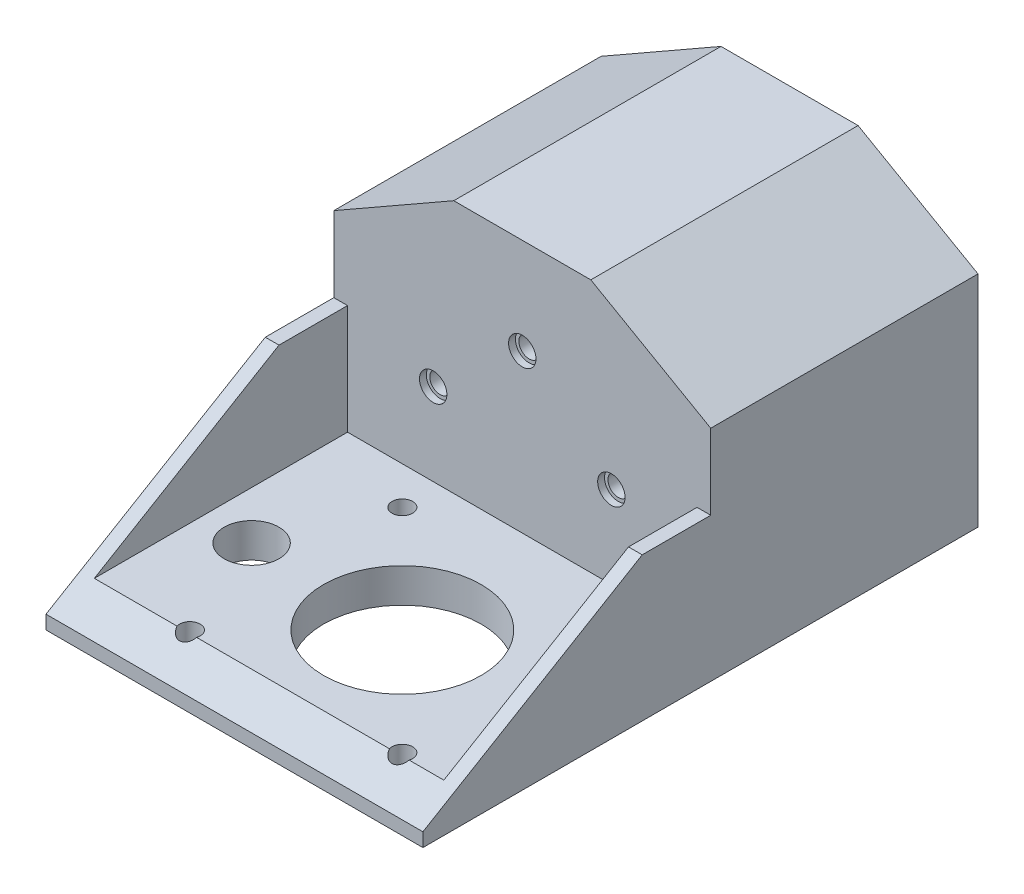
SolidWorks part; units mm, degrees
material "ABS"
ref_plane "Front Plane" through (0, 0, 0) normal (0, 0, 1) x (1, 0, 0)
ref_plane "Top Plane" through (0, 0, 0) normal (0, 1, 0) x (1, 0, 0)
ref_plane "Right Plane" through (0, 0, 0) normal (1, 0, 0) x (0, 0, -1)
sketch "Sketch1" plane through (0, 0, 0) normal (0, 0, 1) x (1, 0, 0)
  line L0 (0, 0) -> (55, 0)
  line L1 (55, 0) -> (55, 32)
  line L2 (55, 32) -> (37.5, 42)
  line L3 (37.5, 42) -> (17.5, 42)
  line L4 (17.5, 42) -> (0, 32)
  line L5 (0, 32) -> (0, 0)
  dimension "D1" = 55
  dimension "D2" = 42
  dimension "D3" = 32
  dimension "D4" = 20
extrude "Boss-Extrude1" add sketch "Sketch1" along normal blind 39
sketch "Sketch2" plane through (0, 0, 39) normal (0, 0, 1) x (1, 0, 0)
  line L0 (55, 0) -> (55, 32) construction
  line L1 (55, 5) -> (0, 5)
  line L2 (55, 5) -> (55, 0)
  line L3 (55, 0) -> (0, 0)
  line L4 (0, 5) -> (0, 0)
  dimension "D1" = 5
extrude "Boss-Extrude2" add sketch "Sketch2" along normal blind 42
sketch "Sketch3" plane through (0, 5, 0) normal (0, 1, 0) x (1, 0, 0)
  line L0 (55, -81) -> (55, -39) construction
  line L5 (31, -60) -> (31, -18) construction
  line L6 (31, -60) -> (63.5225, -60) construction
  line L8 (55, -39) -> (0, -39) construction
  circle A1 centre (15.5, -44.5) radius 1.5
  circle A2 centre (46.5, -44.5) radius 1.5
  circle A3 centre (46.5, -75.5) radius 1.5
  circle A4 centre (15.5, -75.5) radius 1.5
  circle A5 centre (9, -60) radius 4
  circle A6 centre (31, -60) radius 11.5
  dimension "D2" = 23
  dimension "D3" = 24
  dimension "D4" = 31
  dimension "D5" = 31
  dimension "D6" = 15.5
  dimension "D7" = 15.5
  dimension "D8" = 3
  dimension "D9" = 22
  dimension "D10" = 8
  dimension "D13" = 21
  dimension "D12" = 21
extrude "Cut-Extrude1" cut sketch "Sketch3" against normal through all
sketch "Sketch4" plane through (0, 0, 39) normal (0, 0, 1) x (1, 0, 0)
  line L0 (27.5, 43.7016) -> (27.5, -3.1108) construction
  line L1 (55, 5) -> (55, 32) construction
  line L2 (55, 5) -> (0, 5) construction
  line L3 (37.5, 42) -> (17.5, 42) construction
  line L4 (27.5, 47.161) -> (27.5, -7.3668) construction
  circle A0 centre (27.5, 28) radius 1.5
  circle A1 centre (40.5, 17) radius 1.5
  circle A3 centre (14.5, 17) radius 1.5
  dimension "D2" = 3
  dimension "D3" = 12
  dimension "D5" = 14
  dimension "D6" = 27.5
  dimension "D4" = 13
extrude "Cut-Extrude2" cut sketch "Sketch4" against normal through all
sketch "Sketch5" plane through (0, 0, 39) normal (0, 0, 1) x (1, 0, 0)
  circle A0 centre (27.5, 28) radius 2
  circle A1 centre (40.5, 17) radius 2
  circle A2 centre (14.5, 17) radius 2
  dimension "D1" = 4
extrude "Cut-Extrude3" cut sketch "Sketch5" against normal blind 1
sketch "Sketch6" plane through (0, 5, 0) normal (0, 1, 0) x (1, 0, 0)
  line L0 (55, -81) -> (0, -81) construction
  line L1 (0, -39) -> (2, -39)
  line L2 (0, -39) -> (0, -81)
  line L3 (0, -81) -> (2, -81)
  line L4 (2, -39) -> (2, -81)
  line L5 (55, -39) -> (0, -39) construction
  line L6 (55, -39) -> (53, -39)
  line L7 (55, -39) -> (55, -81)
  line L8 (55, -81) -> (53, -81)
  line L9 (53, -39) -> (53, -81)
  line L10 (55, -81) -> (55, -39) construction
  dimension "D1" = 2
  dimension "D2" = 2
extrude "Boss-Extrude3" add sketch "Sketch6" along normal blind 16
sketch "Sketch7" plane through (55, 0, 0) normal (1, 0, 0) x (0, 0, -1)
  line L0 (-49, 21) -> (-81, 21)
  line L1 (-81, 0) -> (-81, 21) construction
  line L2 (-81, 2) -> (-49, 21)
  line L3 (-81, 21) -> (-39, 21) construction
  line L4 (-81, 21) -> (-81, 2)
  line L5 (-81, 0) -> (0, 0) construction
  dimension "D1" = 2
  dimension "D2" = 32
extrude "Cut-Extrude4" cut sketch "Sketch7" against normal blind 70
equation "\"A\"=55"
equation "\"D1@Sketch1\"=\"A\""
equation "\"D6@Sketch4\"=\"A\"/2"
